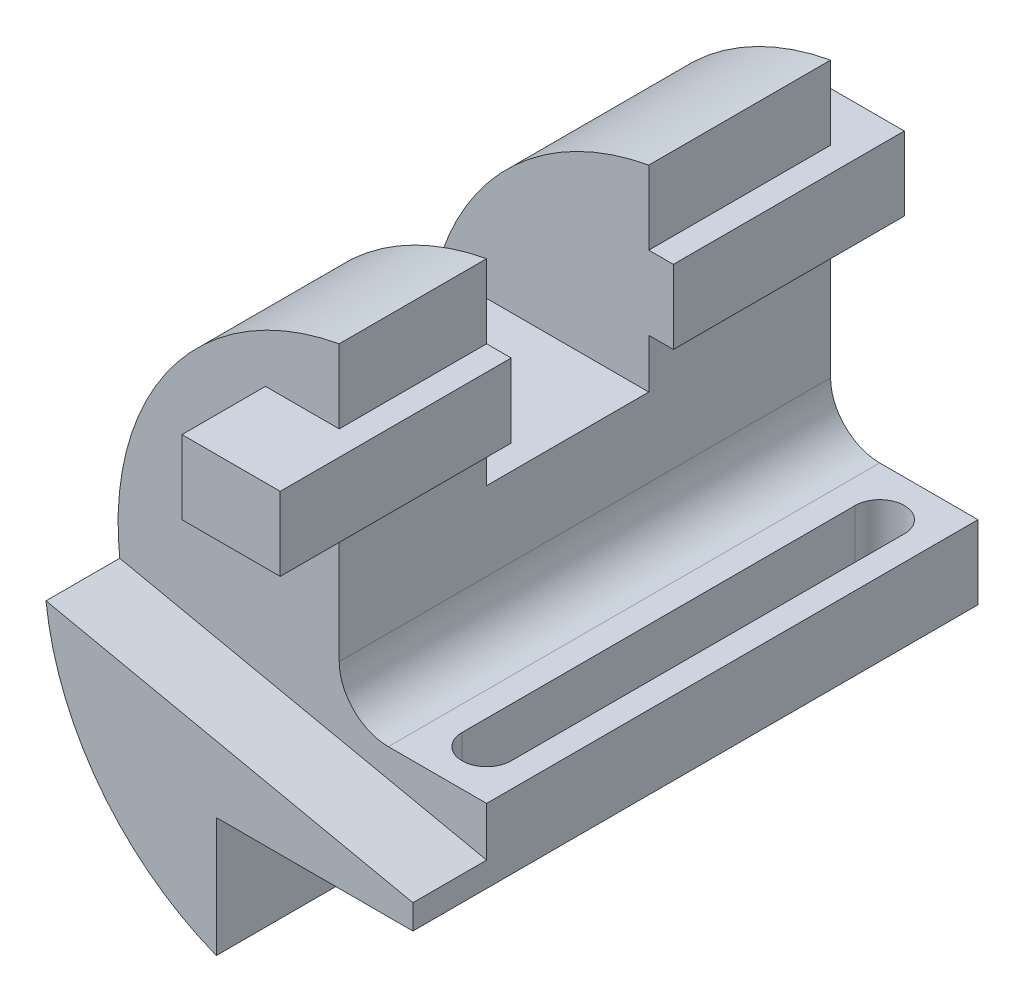
SolidWorks part; units mm, degrees
material "1060 Alloy"
ref_plane "Front Plane" through (0, 0, 0) normal (0, 0, 1) x (1, 0, 0)
ref_plane "Top Plane" through (0, 0, 0) normal (0, 1, 0) x (1, 0, 0)
ref_plane "Right Plane" through (0, 0, 0) normal (1, 0, 0) x (0, 0, -1)
sketch "Sketch2" plane through (0, 0, 0) normal (0, 0, 1) x (1, 0, 0)
  line L0 (0, -79.8984) -> (0, 79.8984) construction
  line L1 (112.6915, 0) -> (-112.6915, 0) construction
  line L2 (-20, -51.2348) -> (-20, -26.9167)
  line L3 (-20, -26.9167) -> (20, -26.9167)
  line L4 (20, -26.9167) -> (20, -11.9167)
  line L5 (20, -11.9167) -> (0, -11.9167)
  line L6 (-10, -1.9167) -> (-10, 54.0833)
  arc A0 (-10, 54.0833) -> (-20, -51.2348) centre (0, 0) ccw
  arc A1 (-10, -1.9167) -> (0, -11.9167) centre (0, -1.9167) ccw
  point P6 (0, 0)
  point P9 (0, 0)
  dimension "D1" = 110
  dimension "D7" = 10
  dimension "D2" = 10
  dimension "D3" = 20
  dimension "D4" = 15
  dimension "D5" = 40
  dimension "D6" = 66
extrude "Boss-Extrude1" add sketch "Sketch2" along normal blind 115
sketch "Sketch3" plane through (0, 0, 115) normal (0, 0, 1) x (1, 0, 0)
  line L0 (-54.6667, -6.0458) -> (20, -21.9167)
  line L1 (20, -26.9167) -> (20, -11.9167) construction
  line L3 (-10, 54.0833) -> (-10, -1.9167)
  line L4 (0, -11.9167) -> (20, -11.9167)
  line L5 (20, -11.9167) -> (20, -21.9167)
  arc A0 (-10, 54.0833) -> (-20, -51.2348) centre (0, 0) ccw construction
  arc A1 (-54.6667, -6.0458) -> (-10, 54.0833) centre (0, 0) cw
  arc A2 (-10, -1.9167) -> (0, -11.9167) centre (0, -1.9167) ccw
  dimension "D3" = 55
  dimension "D1" = 5
  dimension "D2" = 78
extrude "Cut-Extrude1" cut sketch "Sketch3" against normal blind 15
sketch "Sketch4" plane through (0, -11.9167, 0) normal (0, 1, 0) x (1, 0, 0)
  line L0 (10, -10) -> (10, -90) construction
  line L1 (15, -10) -> (15, -90)
  line L2 (5, -10) -> (5, -90)
  line L4 (20, -100) -> (0, -100) construction
  line L5 (20, -100) -> (20, 0) construction
  arc A0 (15, -10) -> (5, -10) centre (10, -10) ccw
  arc A1 (5, -90) -> (15, -90) centre (10, -90) ccw
  point P2 (10, -50)
  dimension "D1" = 80
  dimension "D2" = 10
  dimension "D3" = 10
  dimension "D4" = 10
extrude "Cut-Extrude2" cut sketch "Sketch4" against normal blind 58
sketch "Sketch6" plane through (-10, 0, 0) normal (1, 0, 0) x (0, 0, -1)
  line L0 (-100, 54.0833) -> (0, 54.0833) construction
  line L1 (-70, 54.0833) -> (-37, 54.0833)
  line L2 (-70, 54.0833) -> (-70, 14.0833)
  line L3 (-70, 14.0833) -> (-37, 14.0833)
  line L4 (-37, 54.0833) -> (-37, 14.0833)
  dimension "D1" = 33
  dimension "D2" = 30
  dimension "D3" = 40
extrude "Cut-Extrude3" cut sketch "Sketch6" against normal blind 58
sketch "Sketch7" plane through (-10, 0, 0) normal (1, 0, 0) x (0, 0, -1)
  line L0 (-37, 14.0833) -> (-37, 54.0833) construction
  line L1 (-37, 39.0833) -> (10, 39.0833)
  line L2 (-37, 39.0833) -> (-37, 24.0833)
  line L3 (-37, 24.0833) -> (10, 24.0833)
  line L4 (10, 39.0833) -> (10, 24.0833)
  dimension "D1" = 15
  dimension "D2" = 47
  dimension "D3" = 10
extrude "Boss-Extrude2" add sketch "Sketch7" along normal blind 5 and the other way blind 15
sketch "Sketch8" plane through (-10, 0, 0) normal (1, 0, 0) x (0, 0, -1)
  line L0 (-70, 54.0833) -> (-70, 14.0833) construction
  line L1 (-117, 39.0833) -> (-70, 39.0833)
  line L2 (-117, 39.0833) -> (-117, 24.0833)
  line L3 (-117, 24.0833) -> (-70, 24.0833)
  line L4 (-70, 39.0833) -> (-70, 24.0833)
  point P6 (-117, 31.5833)
  dimension "D1" = 47
  dimension "D2" = 15
  dimension "D3" = 10
extrude "Boss-Extrude3" add sketch "Sketch8" along normal blind 5 and the other way blind 15
